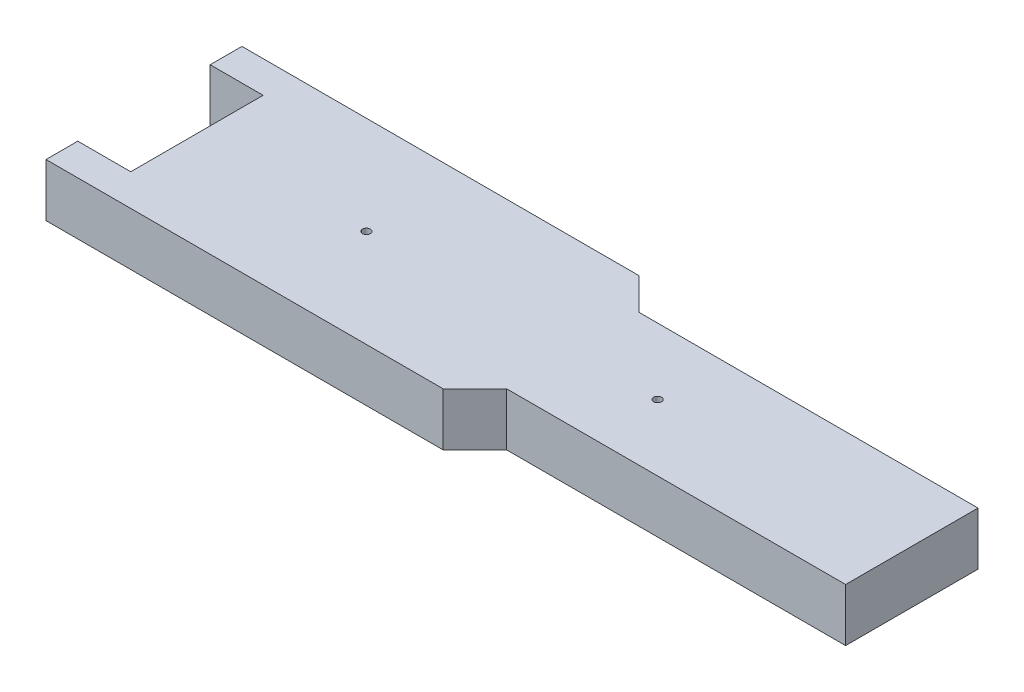
SolidWorks part; units mm, degrees
material "Сосна"
ref_plane "Спереди" through (0, 0, 0) normal (0, 0, 1) x (1, 0, 0)
ref_plane "Сверху" through (0, 0, 0) normal (0, 1, 0) x (1, 0, 0)
ref_plane "Справа" through (0, 0, 0) normal (1, 0, 0) x (0, 0, -1)
sketch "Эскиз1" plane through (0, 0, 0) normal (0, 1, 0) x (1, 0, 0)
  line L0 (0, 31) -> (75, 31)
  line L1 (75, 31) -> (81, 25)
  line L2 (81, 25) -> (145, 25)
  line L3 (145, 25) -> (145, 0)
  line L4 (145, 0) -> (81, 0)
  line L5 (81, 0) -> (75, -6)
  line L6 (75, -6) -> (0, -6)
  line L7 (0, -6) -> (0, 0)
  line L8 (0, 0) -> (10, 0)
  line L9 (10, 0) -> (10, 25)
  line L10 (10, 25) -> (0, 25)
  line L11 (0, 25) -> (0, 31)
  dimension "D1" = 145
  dimension "D2" = 75
  dimension "D3" = 25
  dimension "D4" = 25
  dimension "D5" = 37
  dimension "D6" = 10
extrude "Бобышка-Вытянуть1" add sketch "Эскиз1" along normal blind 10
sketch "Эскиз2" plane through (0, 10, 0) normal (0, 1, 0) x (1, 0, 0)
  line L0 (0, 31) -> (0, 25) construction
  line L1 (75, 31) -> (0, 31) construction
  circle A0 centre (42, 12.5) radius 0.75
  dimension "D1" = 1.5
  dimension "D2" = 42
  dimension "D3" = 18.5
extrude "Вырез-Вытянуть1" cut sketch "Эскиз2" against normal through all
pattern_linear "Линейный массив1" count 2 spacing 55 along (1, 0, 0) of "Вырез-Вытянуть1"
